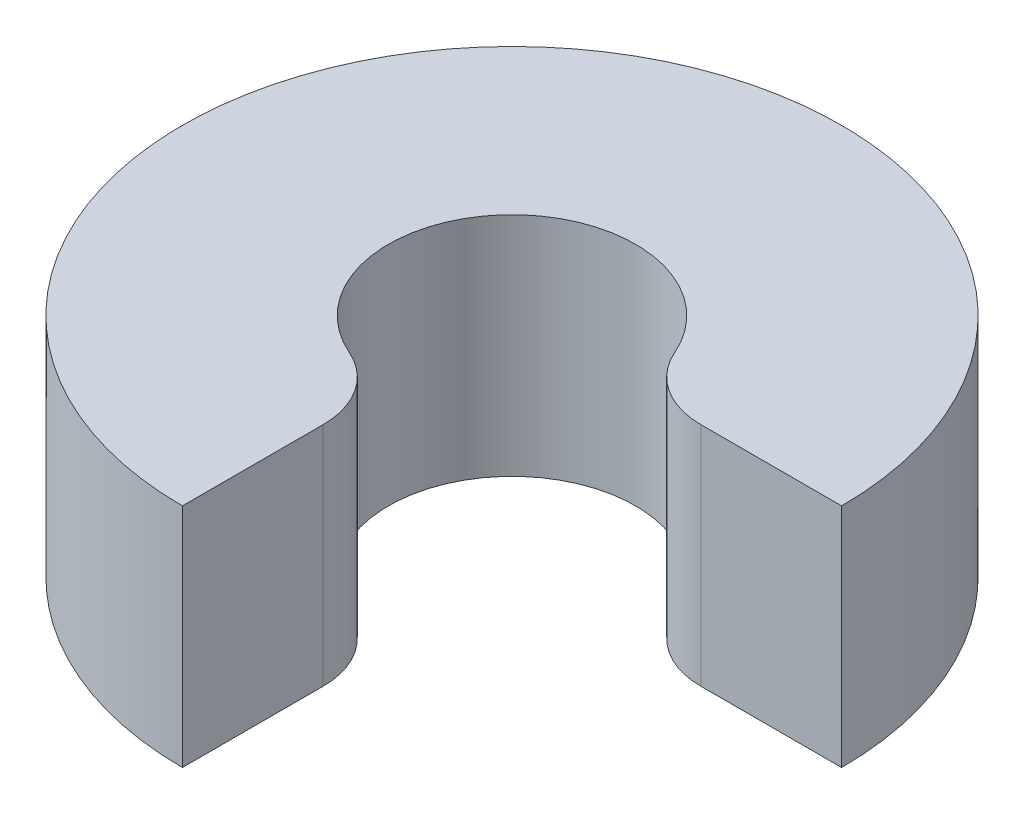
SolidWorks part; units mm, degrees
ref_plane "Alzado" through (0, 0, 0) normal (0, 0, 1) x (1, 0, 0)
ref_plane "Planta" through (0, 0, 0) normal (0, 1, 0) x (1, 0, 0)
ref_plane "Vista lateral" through (0, 0, 0) normal (1, 0, 0) x (0, 0, -1)
sketch "Croquis1" plane through (0, 0, 0) normal (0, 1, 0) x (1, 0, 0)
  line L0 (1.5, 0) -> (4, 0)
  line L1 (0, -1.5) -> (0, -4)
  arc A0 (1.5, 0) -> (0, -1.5) centre (0, 0) ccw
  arc A1 (4, 0) -> (0, -4) centre (0, 0) ccw
  dimension "D1" = 3
  dimension "D2" = 8
  dimension "D3" = 90
extrude "Saliente-Extruir1" add sketch "Croquis1" along normal blind 2.75
fillet "Redondeo1" radius 1 2 edges at (0, 1.375, 1.5) (1.5, 1.375, 0)
